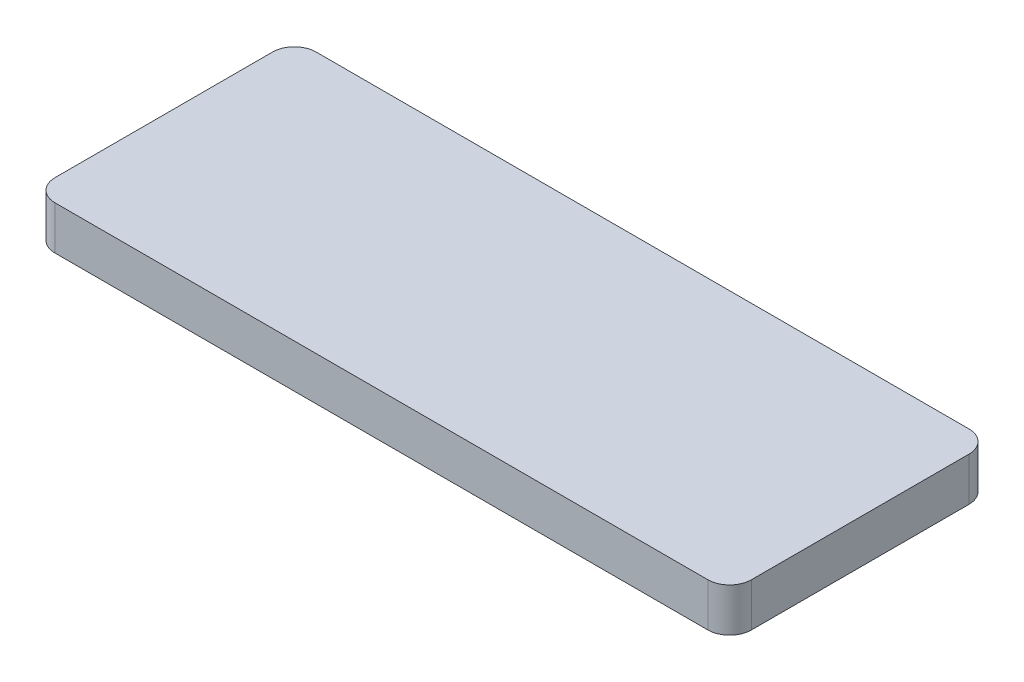
SolidWorks part; units mm, degrees
ref_plane "Front Plane" through (0, 0, 0) normal (0, 0, 1) x (1, 0, 0)
ref_plane "Top Plane" through (0, 0, 0) normal (0, 1, 0) x (1, 0, 0)
ref_plane "Right Plane" through (0, 0, 0) normal (1, 0, 0) x (0, 0, -1)
sketch "Sketch1" plane through (0, 0, 0) normal (0, 1, 0) x (1, 0, 0)
  line L1 (-80, -30) -> (80, -30)
  line L2 (-80, -30) -> (-80, 30)
  line L3 (-80, 30) -> (80, 30)
  line L4 (80, -30) -> (80, 30)
  line L5 (-80, -30) -> (80, 30) construction
  line L6 (-80, 30) -> (80, -30) construction
  point P0 (0, 0)
  dimension "D1" = 160
  dimension "D2" = 60
extrude "Boss-Extrude1" add sketch "Sketch1" along normal blind 10
fillet "Fillet1" radius 5 4 edges at (80, 5, -30) (80, 5, 30) (-80, 5, 30) (-80, 5, -30)
